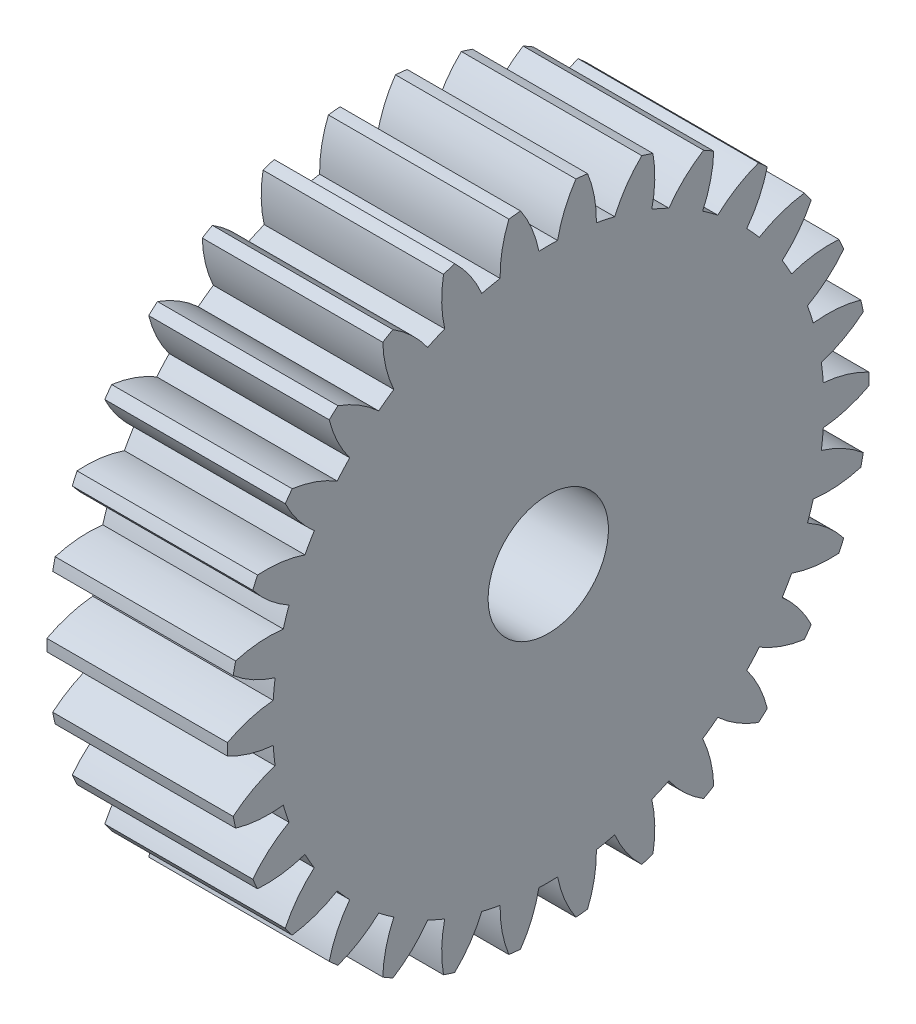
SolidWorks part; units mm, degrees
ref_plane "Plane1" through (0, 0, 0) normal (0, 0, 1) x (1, 0, 0)
ref_plane "Plane2" through (0, 0, 0) normal (0, 1, 0) x (1, 0, 0)
ref_plane "Plane3" through (0, 0, 0) normal (1, 0, 0) x (0, 0, -1)
sketch "HoldingSke" plane through (0, 0, 0) normal (0, 1, 0) x (1, 0, 0)
  line L0 (0, 0) -> (0.866, -0.5)
  line L1 (-15, 0) -> (100, 0) construction
  line L2 (0, 0) -> (-2.1039, 2.3779)
  line L3 (0, 0) -> (-11.863, 4.5341)
  line L4 (0, 0) -> (7.479, 4.318)
  line L5 (0, 0) -> (-46.8476, -17.4728)
  line L6 (0, 0) -> (-7.4607, -5.0337)
  line L7 (-2.1039, 2.3779) -> (8.6586, 51.2059)
  line L8 (-76.2, 54.61) -> (-75.2, 54.61)
  line L9 (-71.009, 38.7566) -> (-53.1078, 45.2721)
  line L10 (-76.2, 71.12) -> (104.1128, 71.12)
  line L11 (0, 0) -> (-9, 0)
  line L12 (-76.2, 101.6) -> (-76.162, 101.6)
  line L13 (24.9733, 27.94) -> (52.9518, 28.4284)
  line L14 (24.9733, 27.94) -> (24.9743, 27.94)
  line L15 (24.9733, 27.94) -> (100.4006, 29.5858)
  line L16 (-63.627, -1) -> (-12.827, -1)
  circle A0 centre (0, 0) radius 3
  circle A1 centre (0, 0) radius 13.749
  circle A2 centre (0, 0) radius 37.5
  circle A3 centre (0, 0) radius 3
  dimension "MHD" = 27.498
  dimension "Hub_dia" = 75
  dimension "Bore" = 6
  dimension "MBD" = 6
  dimension "Num_teeth" = 30
  dimension "Pitch" = 1
  dimension "Overall_len" = 50
  dimension "Show_teeth" = 30
  dimension "Thickness" = 9
  dimension "OAL" = 50.0001
  dimension "T_dim" = 1
  dimension "Ap" = 20
  dimension "H" = 19.05
  dimension "Pitch_radius" = 180.3128
  dimension "Width" = 9
  dimension "Backlash" = 0.038
  dimension "Addendum_fac" = 1
  dimension "Dedendum_fac" = 1.25
  dimension "Clearance_fac" = 0.25
  dimension "Dedendum_add" = 0.001
  dimension "Module" = 1
sketch "BasProSke" plane through (0, 0, 0) normal (0, 1, 0) x (1, 0, 0)
  line L0 (-10, 0) -> (60, 0) construction
  line L1 (0, 0) -> (0, 16)
  line L2 (0, 0) -> (9, 0)
  line L3 (9, 0) -> (9, 16)
  line L4 (9, 16) -> (0, 16)
  dimension "Thickness" = 9
  dimension "Diameter" = 32
revolve "Base-Revolve" add sketch "BasProSke" angle 360 about L0
sketch "TooCutSke" plane through (0, 0, 0) normal (1, 0, 0) x (0, 0, -1)
  line L1 (0, 0) -> (0, 107) construction
  line L2 (0, 0) -> (-0.8515, 14.9758) construction
  line L3 (0, 0) -> (-3.1323, 29.8014) construction
  line L4 (-0.8515, 14.9758) -> (-1.5661, 14.9007) construction
  arc A0 (0.4664, 13.7411) -> (-0.4664, 13.7411) centre (0, 0) ccw
  arc A1 (1.3975, 15.9644) -> (-1.3975, 15.9644) centre (0, 0) ccw
  circle A2 centre (0, 0) radius 15 construction
  circle A3 centre (0, 0) radius 14.0954 construction
  arc A4 (-0.4664, 13.7411) -> (-1.3975, 15.9644) centre (-6.3534, 12.5823) ccw
  arc A5 (1.3975, 15.9644) -> (0.4664, 13.7411) centre (6.3534, 12.5823) ccw
  dimension "Root_dia" = 27.498
  dimension "Overcut_dia" = 32.0508
  dimension "Pitch_dia" = 30
  dimension "Base_dia" = 28.1908
  dimension "Flank_rad" = 6
  dimension "Half_ang" = 6
  dimension "Half_CT" = 0.7185
extrude "ToothCut" cut sketch "TooCutSke" along normal through all
fillet "Breaks" [suppressed] radius 0.02
fillet "RootFillets" [suppressed] radius 0.251
pattern_circular "TeethCuts" count 30 every 12 about axis through (-10, 0, 0) along (1, 0, 0) of "ToothCut", "RootFillets", "Breaks"
sketch "HubNeaOneSke" plane through (0, 0, 0) normal (-1, 0, 0) x (0, 0, 1)
  circle A0 centre (0, 0) radius 13.749
  dimension "Diameter" = 27.498
extrude "HubNearOne" [suppressed] add sketch "HubNeaOneSke" along normal blind 41.0001
sketch "HubNeaBotSke" plane through (0, 0, 0) normal (-1, 0, 0) x (0, 0, 1)
  circle A0 centre (0, 0) radius 13.749
  dimension "Diameter" = 27.498
extrude "HubNearBoth" [suppressed] add sketch "HubNeaBotSke" along normal blind 20.5
ref_plane "FarPln" through (9, 0, 0) normal (1, 0, 0) x (0, 0, -1)
sketch "HubFarSke" plane through (9, 0, 0) normal (1, 0, 0) x (0, 0, -1)
  circle A0 centre (0, 0) radius 13.749
  dimension "Diameter" = 27.498
extrude "HubFar" [suppressed] add sketch "HubFarSke" along normal blind 20.5
sketch "BorSke" plane through (0, 0, 0) normal (1, 0, 0) x (0, 0, -1)
  circle A0 centre (0, 0) radius 3
  dimension "Diameter" = 6
extrude "Bore" cut sketch "BorSke" along normal mid plane 100.0001
sketch "KeySke" plane through (0, 0, 0) normal (1, 0, 0) x (0, 0, -1)
  line L0 (-1, 0) -> (-1, 4)
  line L1 (-1, 4) -> (1, 4)
  line L2 (1, 4) -> (1, 0)
  line L3 (0, 0) -> (0, 34) construction
  line L4 (-1, 0) -> (1, 0)
  dimension "Offset" = 4
  dimension "Width" = 2
extrude "Keyway" [suppressed] cut sketch "KeySke" along normal mid plane 100.0001
pattern_circular "Keyway2" [suppressed] count 2 every 90 about axis through (-10, 0, 0) along (1, 0, 0)
equation "' \"Module@HoldingSke\" = 6.35"
equation "' \"Num_teeth@HoldingSke\" = 12"
equation "' \"Ap@HoldingSke\" =  20"
equation "' \"Ap@HoldingSke\" = 20"
equation "' \"Width@HoldingSke\" = 0.5 * 25.4"
equation "' \"Hub_dia@HoldingSke\"= 1 * 25.4"
equation "' \"Hub_dia@HoldingSke\" = 1 * 25.4"
equation "' \"Overall_len@HoldingSke\" = 1.0 * 25.4"
equation "' \"Bore@HoldingSke\" = 0.75 * 25.4"
equation "' \"T_dim@HoldingSke\" = 0.1 * 25.4"
equation "' \"Width@KeySke\" = 0.25 * 25.4"
equation "' \"Show_teeth@HoldingSke\" = 13"
equation "' \"Backlash@HoldingSke\" = 0.009 * 25.4"
equation "' \"Addendum_fac@HoldingSke\" = 1.0"
equation "' \"Dedendum_fac@HoldingSke\" = 1.25"
equation "' \"Dedendum_add@HoldingSke\" = 0.00005 * 25.4"
equation "' \"Clearance_fac@HoldingSke\" = 0.25"
equation "\"Pitch@HoldingSke\" = 1 / \"Module@HoldingSke\""
equation "\"Overcut_dia@TooCutSke\" = (\"Num_teeth@HoldingSke\" + 2 * \"Addendum_fac@HoldingSke\") / \"Pitch@HoldingSke\" + 0.002 * 25.4"
equation "\"Pitch_dia@TooCutSke\" = \"Num_teeth@HoldingSke\" / \"Pitch@HoldingSke\""
equation "\"Base_dia@TooCutSke\" = \"Num_teeth@HoldingSke\" / \"Pitch@HoldingSke\" * cos((\"Ap@HoldingSke\"  * 3.14159265 / 180))"
equation "\"Root_dia@TooCutSke\" = (\"Num_teeth@HoldingSke\" + 2) / \"Pitch@HoldingSke\" - 2 * (\"Addendum_fac@HoldingSke\" + \"Dedendum_fac@HoldingSke\") / \"Pitch@HoldingSke\" - \"Dedendum_add@HoldingSke\" * 2"
equation "\"Half_ang@TooCutSke\" = 180 / \"Num_teeth@HoldingSke\""
equation "\"Half_CT@TooCutSke\" = \"Num_teeth@HoldingSke\" / \"Pitch@HoldingSke\" * sin((3.14159265 / 2 / \"Num_teeth@HoldingSke\")) / 2 - 7 * \"Backlash@HoldingSke\" / 4"
equation "\"Flank_rad@TooCutSke\" = \"Num_teeth@HoldingSke\" / \"Pitch@HoldingSke\" / 5"
equation "\"Radius@RootFillets\" = \"Clearance_fac@HoldingSke\" / \"Pitch@HoldingSke\" + \"Dedendum_add@HoldingSke\""
equation "\"Break_rad@Breaks\" = 0.02 / \"Pitch@HoldingSke\""
equation "\"Thickness@HoldingSke\" = \"Width@HoldingSke\""
equation "\"OAL@HoldingSke\" = \"Thickness@HoldingSke\""
equation "\"MHD@HoldingSke\" = (\"Num_teeth@HoldingSke\" + 2) / \"Pitch@HoldingSke\" - 2 * (\"Addendum_fac@HoldingSke\" + \"Dedendum_fac@HoldingSke\")  / \"Pitch@HoldingSke\" - \"Dedendum_add@HoldingSke\" * 2"
equation "\"MBD@HoldingSke\" = (\"Num_teeth@HoldingSke\" + 2) / \"Pitch@HoldingSke\" - 2 * (\"Addendum_fac@HoldingSke\" + \"Dedendum_fac@HoldingSke\")  / \"Pitch@HoldingSke\" - \"Dedendum_add@HoldingSke\" * 2 - 0.002 * 25.4"
equation "\"MHD@HoldingSke\" = ((sgn( \"MHD@HoldingSke\" - \"Hub_dia@HoldingSke\" )-1)*( \"MHD@HoldingSke\" - \"Hub_dia@HoldingSke\" ))/-2+ \"Hub_dia@HoldingSke\""
equation "\"MBD@HoldingSke\" = ((sgn( \"MBD@HoldingSke\" - \"Bore@HoldingSke\" )-1)*( \"MBD@HoldingSke\" - \"Bore@HoldingSke\" ))/-2+ \"Bore@HoldingSke\""
equation "\"OAL@HoldingSke\" = ((sgn( \"OAL@HoldingSke\" - \"Overall_len@HoldingSke\" )+1)*( \"OAL@HoldingSke\" - \"Overall_len@HoldingSke\" ))/2 + \"Overall_len@HoldingSke\" + 0.000002 * 25.4"
equation "\"Num_teeth@TeethCuts\" = int( \"Show_teeth@HoldingSke\" ) + 1"
equation "\"Num_teeth@TeethCuts\" = ((sgn( \"Num_teeth@TeethCuts\" - \"Num_teeth@HoldingSke\" )-1)*( \"Num_teeth@TeethCuts\" - \"Num_teeth@HoldingSke\" ))/-2+ \"Num_teeth@HoldingSke\""
equation "\"Num_teeth@TeethCuts\" = ((sgn( \"Num_teeth@TeethCuts\" - 2.0)+1)*( \"Num_teeth@TeethCuts\" - 2.0))/2 +2.0"
equation "\"Angle@TeethCuts\" = 360.0 / \"Num_teeth@HoldingSke\""
equation "\"Diameter@BasProSke\" = (\"Num_teeth@HoldingSke\" + 2 * \"Addendum_fac@HoldingSke\") / \"Pitch@HoldingSke\""
equation "\"Thickness@BasProSke\"  = \"Thickness@HoldingSke\""
equation "' \"Fillet_rad@BasProSke\" =  \"Thickness@HoldingSke\" * 0.05"
equation "' \"Fillet_rad@BasProSke\" = \"Thickness@HoldingSke\" * 0.05"
equation "\"MHD@HoldingSke\" = ((sgn( \"MHD@HoldingSke\" - \"Root_dia@TooCutSke\" )-1)*( \"MHD@HoldingSke\" - \"Root_dia@TooCutSke\" ))/-2+ \"Root_dia@TooCutSke\""
equation "\"Diameter@HubNeaOneSke\" = \"MHD@HoldingSke\""
equation "\"Length@HubNearOne\" = \"OAL@HoldingSke\" - \"Thickness@BasProSke\""
equation "\"Diameter@HubNeaBotSke\" = \"MHD@HoldingSke\""
equation "\"Length@HubNearBoth\" = ( \"OAL@HoldingSke\" - \"Thickness@BasProSke\" ) / 2.0"
equation "\"Thickness@FarPln\" = \"Thickness@BasProSke\""
equation "\"Diameter@HubFarSke\" = \"MHD@HoldingSke\""
equation "\"Length@HubFar\" = ( \"OAL@HoldingSke\" - \"Thickness@BasProSke\" ) / 2.0"
equation "\"Diameter@BorSke\" = \"MBD@HoldingSke\""
equation "\"D1@Bore\" = \"OAL@HoldingSke\" * 2.0"
equation "\"D1@Keyway\" = \"OAL@HoldingSke\" * 2.0"
equation "\"Offset@KeySke\" = \"T_dim@HoldingSke\" + \"MBD@HoldingSke\" / 2.0"
